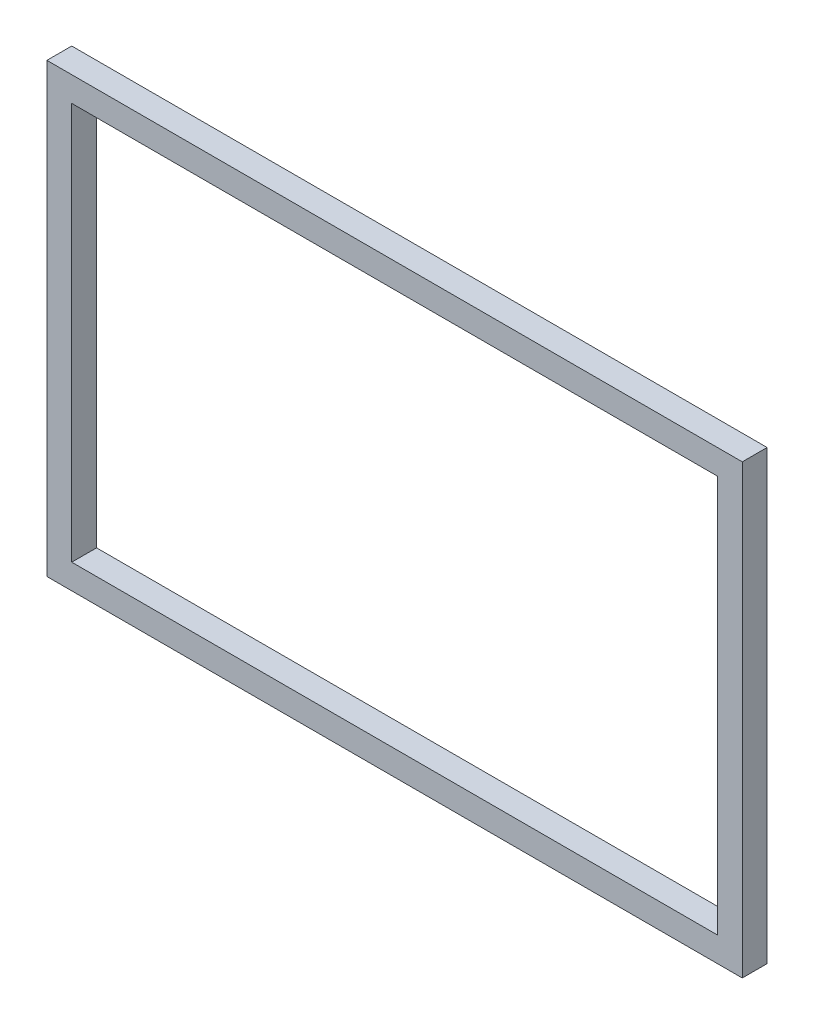
SolidWorks part; units mm, degrees
ref_plane "Front Plane" through (0, 0, 0) normal (0, 0, 1) x (1, 0, 0)
ref_plane "Top Plane" through (0, 0, 0) normal (0, 1, 0) x (1, 0, 0)
ref_plane "Right Plane" through (0, 0, 0) normal (1, 0, 0) x (0, 0, -1)
sketch "Sketch1" plane through (0, 0, 0) normal (0, 0, 1) x (1, 0, 0)
  line L1 (-47.4445, -153.2258) -> (232.5555, -153.2258)
  line L2 (-47.4445, -153.2258) -> (-47.4445, 26.7742)
  line L3 (-47.4445, 26.7742) -> (232.5555, 26.7742)
  line L4 (232.5555, -153.2258) -> (232.5555, 26.7742)
  dimension "D1" = 280
  dimension "D2" = 180
extrude "Extrude-Thin1" add sketch "Sketch1" along normal blind 10 thin thin type one direction reverse wall 10
